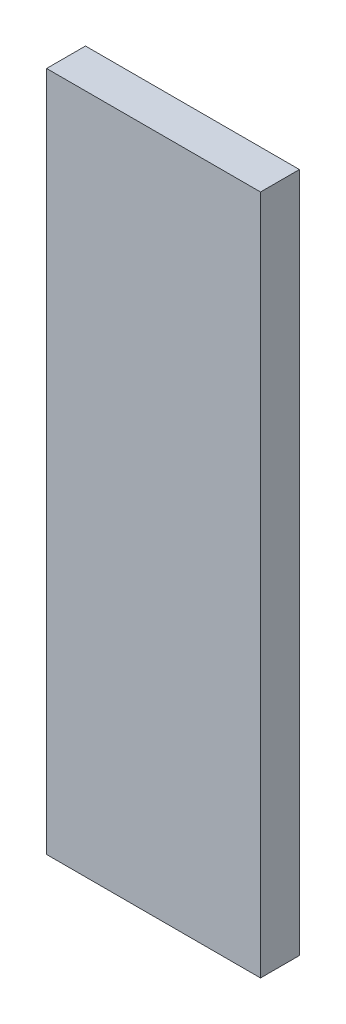
SolidWorks part; units mm, degrees
ref_plane "Front Plane" through (0, 0, 0) normal (0, 0, 1) x (1, 0, 0)
ref_plane "Top Plane" through (0, 0, 0) normal (0, 1, 0) x (1, 0, 0)
ref_plane "Right Plane" through (0, 0, 0) normal (1, 0, 0) x (0, 0, -1)
sketch "Sketch1" plane through (0, 0, 0) normal (0, 0, 1) x (1, 0, 0)
  line L1 (27.94, -88.9) -> (-27.94, -88.9)
  line L2 (27.94, -88.9) -> (27.94, 88.9)
  line L3 (27.94, 88.9) -> (-27.94, 88.9)
  line L4 (-27.94, -88.9) -> (-27.94, 88.9)
  line L5 (27.94, -88.9) -> (-27.94, 88.9) construction
  line L6 (27.94, 88.9) -> (-27.94, -88.9) construction
  point P0 (0, 0)
  dimension "D1" = 177.8
  dimension "D2" = 55.88
extrude "Boss-Extrude1" add sketch "Sketch1" along normal mid plane 10.16
